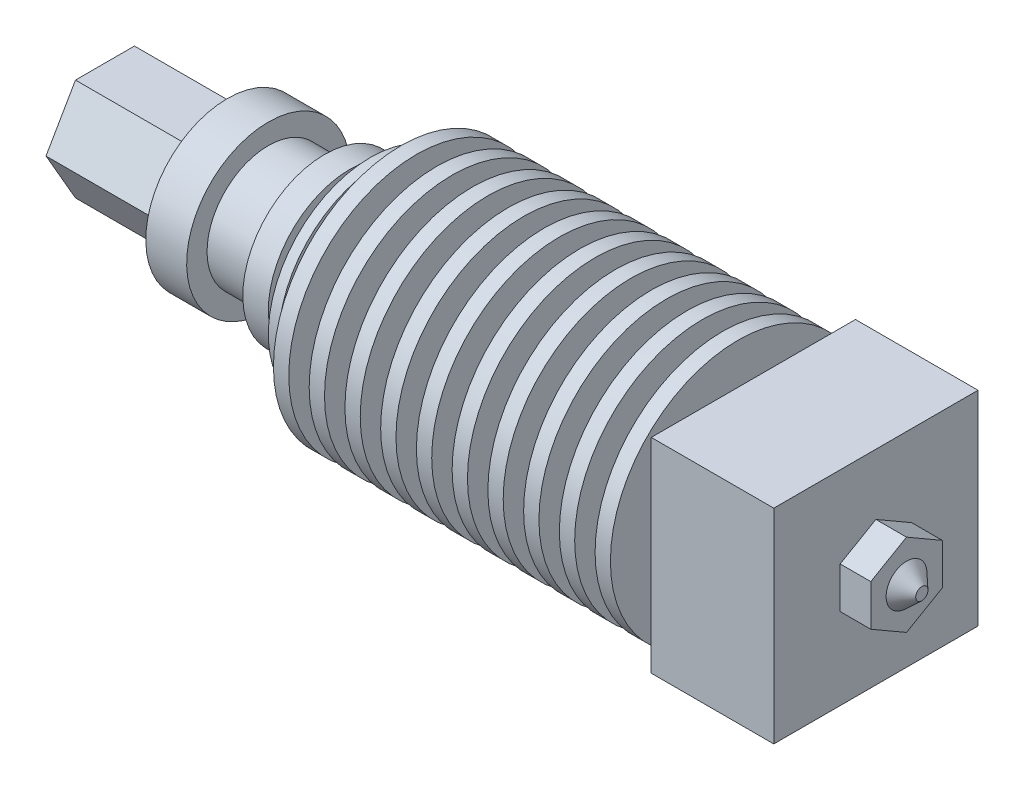
SolidWorks part; units mm, degrees
ref_plane "前基準面" through (0, 0, 0) normal (0, 0, 1) x (1, 0, 0)
ref_plane "上基準面" through (0, 0, 0) normal (0, 1, 0) x (1, 0, 0)
ref_plane "右基準面" through (0, 0, 0) normal (1, 0, 0) x (0, 0, -1)
sketch "草圖1" plane through (0, 0, 0) normal (0, 0, 1) x (1, 0, 0)
  line L0 (0, 0) -> (-50, 0)
  line L1 (0, 0) -> (0, 12.5)
  line L2 (0, 12.5) -> (-1.5, 12.5)
  line L3 (-1.5, 12.5) -> (-1.5, 7.5)
  line L4 (-1.5, 7.5) -> (-3.5, 7.5)
  line L5 (-3.5, 7.5) -> (-3.5, 12.5)
  line L6 (-3.5, 7.5) -> (-3.5, 12.5)
  line L7 (-5, 12.5) -> (-5, 7.5)
  line L8 (-5, 7.5) -> (-7, 7.5)
  line L9 (-7, 7.5) -> (-7, 12.5)
  line L10 (-3.5, 12.5) -> (-5, 12.5)
  line L11 (-7, 7.5) -> (-7, 12.5)
  line L12 (-8.5, 12.5) -> (-8.5, 7.5)
  line L13 (-8.5, 7.5) -> (-10.5, 7.5)
  line L14 (-10.5, 7.5) -> (-10.5, 12.5)
  line L15 (-7, 12.5) -> (-8.5, 12.5)
  line L16 (-10.5, 7.5) -> (-10.5, 12.5)
  line L17 (-12, 12.5) -> (-12, 7.5)
  line L18 (-12, 7.5) -> (-14, 7.5)
  line L19 (-14, 7.5) -> (-14, 12.5)
  line L20 (-10.5, 12.5) -> (-12, 12.5)
  line L21 (-14, 7.5) -> (-14, 12.5)
  line L22 (-15.5, 12.5) -> (-15.5, 7.5)
  line L23 (-15.5, 7.5) -> (-17.5, 7.5)
  line L24 (-17.5, 7.5) -> (-17.5, 12.5)
  line L25 (-14, 12.5) -> (-15.5, 12.5)
  line L26 (-17.5, 7.5) -> (-17.5, 12.5)
  line L27 (-19, 12.5) -> (-19, 7.5)
  line L28 (-19, 7.5) -> (-21, 7.5)
  line L29 (-21, 7.5) -> (-21, 12.5)
  line L30 (-17.5, 12.5) -> (-19, 12.5)
  line L31 (-21, 7.5) -> (-21, 12.5)
  line L32 (-22.5, 12.5) -> (-22.5, 7.5)
  line L33 (-22.5, 7.5) -> (-24.5, 7.5)
  line L34 (-24.5, 7.5) -> (-24.5, 12.5)
  line L35 (-21, 12.5) -> (-22.5, 12.5)
  line L36 (-24.5, 7.5) -> (-24.5, 12.5)
  line L37 (-26, 12.5) -> (-26, 7.5)
  line L38 (-26, 7.5) -> (-28, 7.5)
  line L39 (-28, 7.5) -> (-28, 12.5)
  line L40 (-24.5, 12.5) -> (-26, 12.5)
  line L41 (-28, 7.5) -> (-28, 12.5)
  line L42 (-29.5, 12.5) -> (-29.5, 7.5)
  line L43 (-29.5, 7.5) -> (-31.5, 7.5)
  line L44 (-31.5, 7.5) -> (-31.5, 12.5)
  line L45 (-28, 12.5) -> (-29.5, 12.5)
  line L46 (-31.5, 7.5) -> (-31.5, 12.5)
  line L47 (-33, 12.5) -> (-33, 7.5)
  line L48 (-33, 7.5) -> (-35, 7.5)
  line L49 (-35, 7.5) -> (-35, 10)
  line L50 (-31.5, 12.5) -> (-33, 12.5)
  line L51 (-35, 7.5) -> (-35, 12.5) [skipped]
  line L52 (-35, 10) -> (-36, 10)
  line L53 (-36, 10) -> (-36, 4.5)
  line L54 (-36, 4.5) -> (-38, 4.5)
  line L55 (-38, 4.5) -> (-38, 8)
  line L56 (-38, 8) -> (-40.5, 8)
  line L57 (-40.5, 8) -> (-40.5, 6)
  line L58 (-40.5, 6) -> (-46, 6)
  line L59 (-46, 6) -> (-46, 8)
  line L60 (-46, 8) -> (-50, 8)
  line L61 (-50, 8) -> (-50, 0)
  point P2 (-57.4977, 0)
  point P16 (-53.8909, 0)
  point P67 (-50.5704, 0)
  dimension "D1" = 12.5
  dimension "D2" = 7.5
  dimension "D3" = 1.5
  dimension "D4" = 2
  dimension "D5" = 5
  dimension "D7" = 2
  dimension "D8" = 10
  dimension "D9" = 2.5
  dimension "D10" = 4
  dimension "D11" = 8
  dimension "D12" = 6
  dimension "D13" = 8
  dimension "D14" = 4.5
  dimension "D15" = 1
  dimension "D16" = 5.5
  dimension "D17" = 50
  dimension "D6" = 10
revolve "旋轉1" add sketch "草圖1" angle 360 about L0
sketch "草圖2" plane through (0, 0, 0) normal (1, 0, 0) x (0, 0, -1)
  circle A0 centre (0, 0) radius 3
  dimension "D1" = 6
extrude "填料-伸長1" add sketch "草圖2" along normal blind 1.5
sketch "草圖3" plane through (1.5, 0, 0) normal (1, 0, 0) x (0, 0, -1)
  line L1 (10, 10) -> (-10, 10)
  line L2 (10, 10) -> (10, -10)
  line L3 (10, -10) -> (-10, -10)
  line L4 (-10, 10) -> (-10, -10)
  point P4 (0, 10)
  point P6 (-10, 0)
  dimension "D1" = 20
  dimension "D2" = 20
extrude "填料-伸長2" add sketch "草圖3" along normal blind 12
sketch "草圖4" plane through (13.5, 0, 0) normal (1, 0, 0) x (0, 0, -1)
  line L1 (0, 4.0415) -> (-3.5, 2.0207)
  line L2 (-3.5, 2.0207) -> (-3.5, -2.0207)
  line L3 (-3.5, -2.0207) -> (0, -4.0415)
  line L4 (0, -4.0415) -> (3.5, -2.0207)
  line L5 (3.5, -2.0207) -> (3.5, 2.0207)
  line L6 (3.5, 2.0207) -> (0, 4.0415)
  circle A0 centre (0, 0) radius 3.5 construction
  dimension "D1" = 7
extrude "填料-伸長3" add sketch "草圖4" along normal blind 3
sketch "草圖6" plane through (0, 0, 0) normal (0, 0, 1) x (1, 0, 0)
  line L0 (16.5, 0) -> (18, 0)
  line L1 (16.5, 2.0207) -> (16.5, -2.0207) construction
  line L2 (18, 0) -> (18, 0.6)
  line L3 (18, 0.6) -> (16.5, 2)
  line L4 (16.5, 4.0415) -> (16.5, 2.0207) construction
  line L5 (16.5, 2) -> (16.5, 0)
  dimension "D1" = 2
  dimension "D2" = 1.5
  dimension "D3" = 0.6
revolve "旋轉2" add sketch "草圖6" angle 360 about L0
sketch "草圖7" plane through (-50, 0, 0) normal (-1, 0, 0) x (0, 0, 1)
  line L1 (-5.7735, 0) -> (-2.8868, -5)
  line L2 (-2.8868, -5) -> (2.8868, -5)
  line L3 (2.8868, -5) -> (5.7735, 0)
  line L4 (5.7735, 0) -> (2.8868, 5)
  line L5 (2.8868, 5) -> (-2.8868, 5)
  line L6 (-2.8868, 5) -> (-5.7735, 0)
  circle A0 centre (0, 0) radius 5 construction
  dimension "D1" = 10
extrude "填料-伸長4" add sketch "草圖7" along normal blind 12
